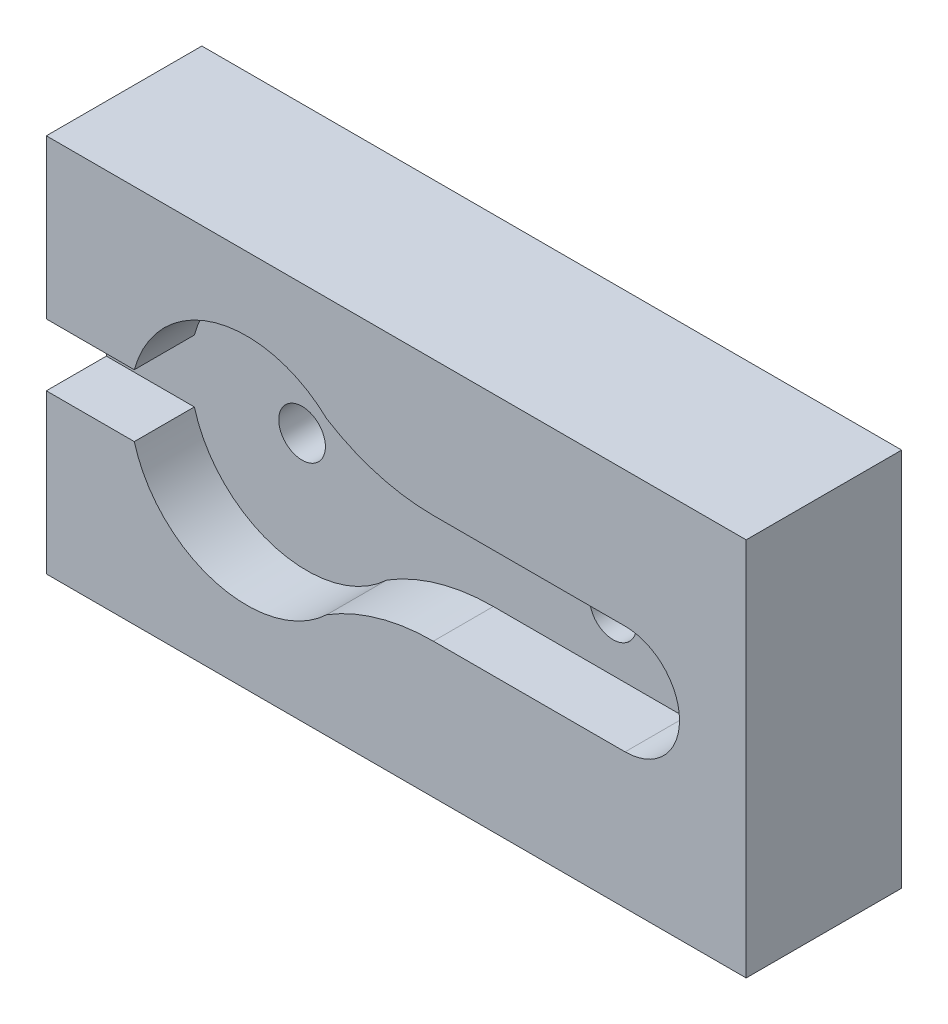
SolidWorks part; units mm, degrees
ref_plane "Front Plane" through (0, 0, 0) normal (1, 0, 0) x (0, 1, 0)
ref_plane "Top Plane" through (0, 0, 0) normal (0, 0, 1) x (0, 1, 0)
ref_plane "Right Plane" through (0, 0, 0) normal (0, 1, 0) x (-1, 0, 0)
sketch "Sketch2" plane through (0, 0, 0) normal (0, 0, 1) x (0, 1, 0)
  line L0 (12.2, 22.5) -> (-12.2, 22.5)
  line L1 (12.2, 22.5) -> (12.2, -22.5)
  line L2 (12.2, -22.5) -> (-12.2, -22.5)
  line L3 (-12.2, 22.5) -> (-12.2, -22.5)
  line L4 (12.2, 22.5) -> (-12.2, -22.5) construction
  line L5 (12.2, -22.5) -> (-12.2, 22.5) construction
  point P0 (0, 0)
  point P6 (0, 0)
  dimension "D1" = 24.4
  dimension "D2" = 45
extrude "Boss-Extrude1" add sketch "Sketch2" along normal blind 10
sketch "Sketch3" plane through (0, 0, 10) normal (0, 0, 1) x (1, 0, 0)
  line L4 (14.7155, 3.5) -> (2.385, 3.5)
  line L5 (-22.5, 0) -> (22.5, 0) construction
  line L6 (-22.5, 12.2) -> (-22.5, -12.2) construction
  line L7 (22.5, -12.2) -> (22.5, 12.2) construction
  line L9 (14.7155, -3.5) -> (2.385, -3.5)
  line L10 (2.385, 3.5) -> (2.385, -3.5) construction
  arc A8 (-4.4615, 5.4489) -> (-4.4615, -5.4489) centre (-9.615, 0) ccw
  arc A9 (2.385, 3.5) -> (-4.4615, 5.4489) centre (2.385, 16.5) cw
  arc A10 (2.385, -3.5) -> (-4.4615, -5.4489) centre (2.385, -16.5) ccw
  arc A11 (14.7155, -3.5) -> (14.7155, 3.5) centre (14.7155, 0) ccw
  dimension "D2" = 15
  dimension "D3" = 24.3305
  dimension "D4" = 13
  dimension "D1" = 12
extrude "Cut-Extrude1" cut sketch "Sketch3" against normal blind 3.86
sketch "Sketch4" plane through (0, 0, 6.14) normal (0, 0, 1) x (1, 0, 0)
  line L0 (-17.115, 0) -> (18.2155, 0) construction
  arc A0 (-4.4615, 5.4489) -> (-4.4615, -5.4489) centre (-9.615, 0) ccw construction
  arc A1 (14.7155, -3.5) -> (14.7155, 3.5) centre (14.7155, 0) ccw construction
  circle A2 centre (10.085, 0) radius 1.5
  circle A3 centre (14.085, 0) radius 1.5
  circle A4 centre (-9.915, 0) radius 1.5
  dimension "D1" = 3
  dimension "D3" = 31.2
  dimension "D4" = 3
  dimension "D2" = 27.2
  dimension "D5" = 7.2
extrude "Cut-Extrude2" cut sketch "Sketch4" against normal through all
sketch "Sketch6" plane through (0, 0, 10) normal (0, 0, 1) x (1, 0, 0)
  line L0 (-22.5, 0) -> (-17.115, 0) construction
  line L1 (-22.5, 12.2) -> (-22.5, -12.2) construction
  line L2 (-22.5, 2) -> (-16.8434, 2)
  line L3 (-22.5, -2) -> (-22.5, 2)
  line L4 (-22.5, -2) -> (-16.8434, -2)
  arc A0 (-4.4615, 5.4489) -> (-4.4615, -5.4489) centre (-9.615, 0) ccw construction
  arc A1 (-4.4615, 5.4489) -> (-4.4615, -5.4489) centre (-9.615, 0) ccw construction
  arc A2 (-16.8434, 2) -> (-16.8434, -2) centre (-9.615, 0) ccw
  dimension "D1" = 2
extrude "Cut-Extrude4" cut sketch "Sketch6" against normal blind 3.86
